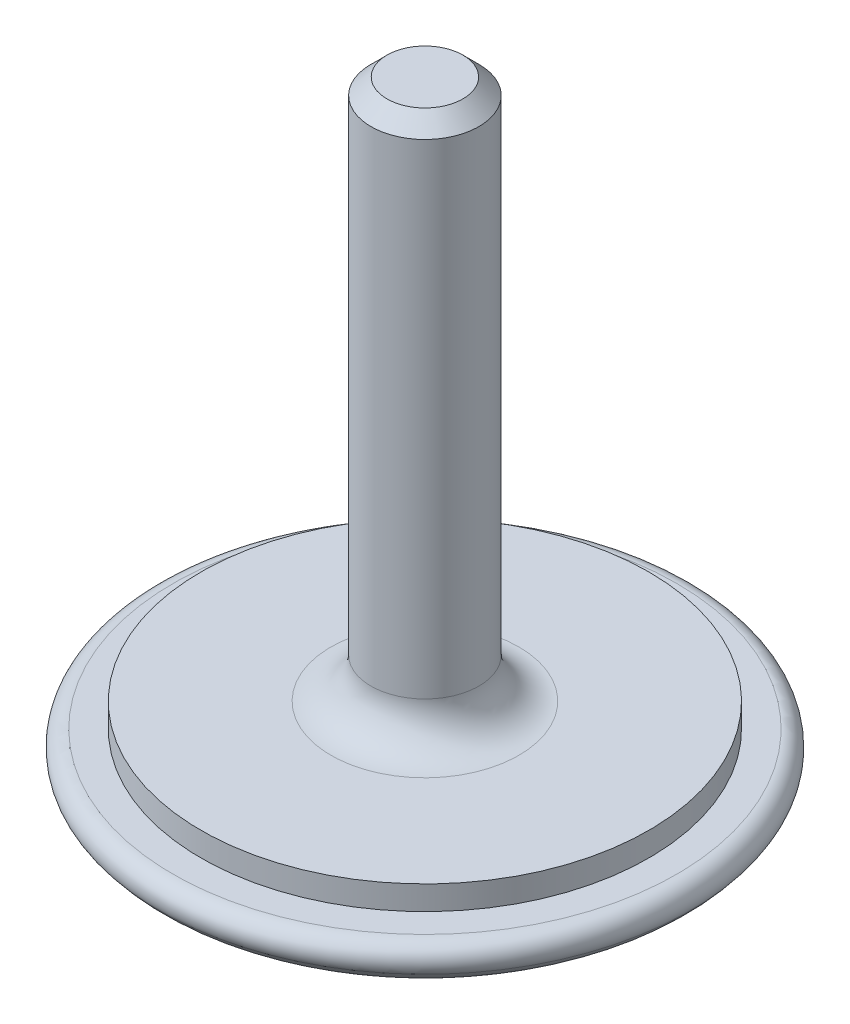
SolidWorks part; units mm, degrees
material "Nylon"
ref_plane "Front Plane" through (0, 0, 0) normal (0, 0, 1) x (1, 0, 0)
ref_plane "Top Plane" through (0, 0, 0) normal (0, 1, 0) x (1, 0, 0)
ref_plane "Right Plane" through (0, 0, 0) normal (1, 0, 0) x (0, 0, -1)
sketch "Sketch1" plane through (0, 0, 0) normal (0, 0, 1) x (1, 0, 0)
  line L0 (3, 0) -> (6.1106, 0)
  line L1 (8.3602, 0.2563) -> (14.8, 1.7431)
  line L3 (14, 4.5) -> (15.75, 4.5)
  line L4 (14, 6) -> (5.875, 6)
  line L5 (3.375, 8.5) -> (3.375, 38.8)
  line L6 (2.375, 39.8) -> (0, 39.8)
  line L7 (0, 0) -> (0, 39.8) construction
  line L8 (2.375, 39.8) -> (3.375, 38.8)
  line L9 (0, 1) -> (0, 39.8)
  line L10 (0, 0) -> (0, -26.7914) construction
  line L17 (14, 4.5) -> (14, 6)
  arc A1 (5.875, 6) -> (3.375, 8.5) centre (5.875, 8.5) cw
  arc A2 (8.3602, 0.2563) -> (6.1106, 0) centre (6.1106, 10) cw
  arc A5 (15.75, 4.5) -> (16.5624, 2.9169) centre (15.75, 3.5) cw
  arc A6 (16.5624, 2.9169) -> (14.8, 1.7431) centre (14.1252, 4.6662) cw
  arc A7 (3, 0) -> (0, 1) centre (0, -4) ccw
  point P15 (7.25, 0)
  point P19 (12.25, 4.75)
  dimension "D5" = 24.5
  dimension "D7" = 10
  dimension "D8" = 6
  dimension "D9" = 2.5
  dimension "D3" = 1.25
  dimension "D10" = 33.5
  dimension "D15" = 5
  dimension "D20" = 28
  dimension "D16" = 1
  dimension "D4" = 3
  dimension "D1" = 6.75
  dimension "D2" = 33.8
  dimension "D6" = 14.5
  dimension "D11" = 45
  dimension "D12" = 1
  dimension "D13" = 33.8
  dimension "D14" = 1.5
  dimension "D18" = 6
  dimension "D21" = 13
  dimension "D24" = 39.8
revolve "Revolve1" add sketch "Sketch1" angle 360 about L7
